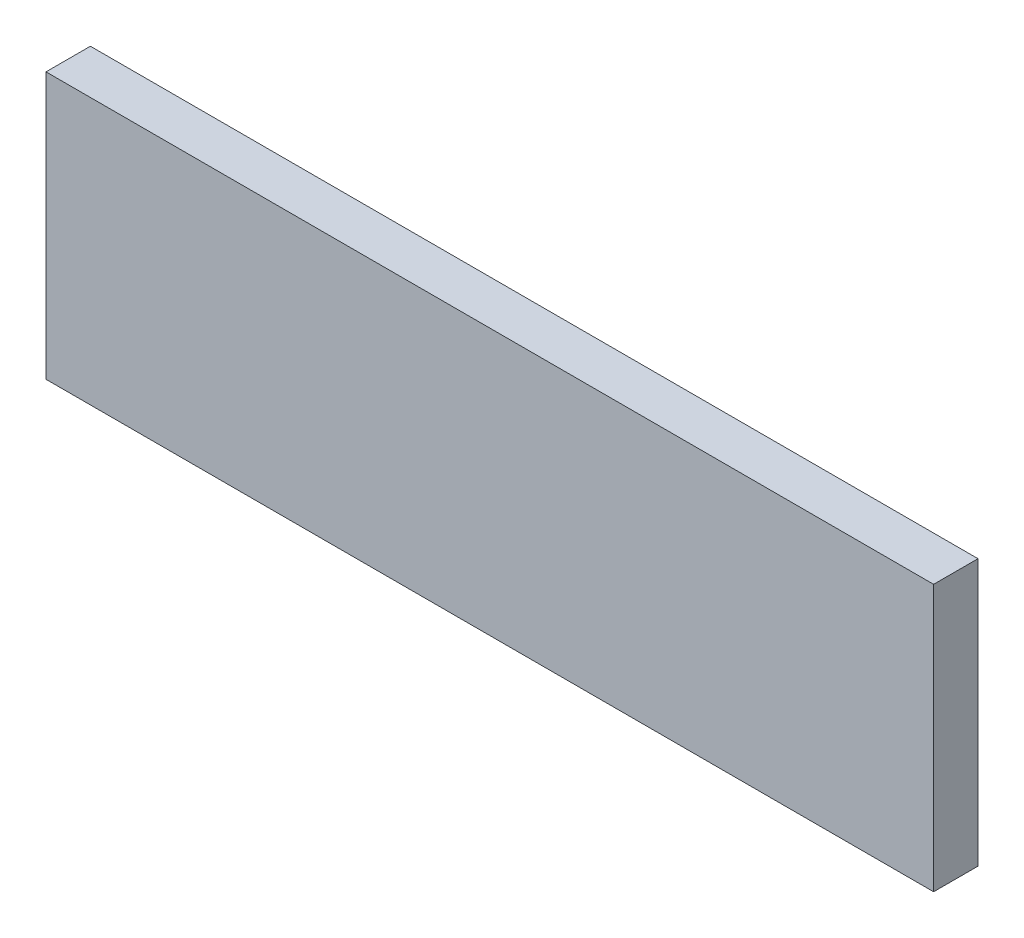
SolidWorks part; units mm, degrees
ref_plane "Front Plane" through (0, 0, 0) normal (0, 0, 1) x (1, 0, 0)
ref_plane "Top Plane" through (0, 0, 0) normal (0, 1, 0) x (1, 0, 0)
ref_plane "Right Plane" through (0, 0, 0) normal (1, 0, 0) x (0, 0, -1)
sketch "Sketch1" plane through (0, 0, 0) normal (0, 1, 0) x (1, 0, 0)
  line L0 (129.3552, 20.4513) -> (-20.6448, 20.4513) construction
  line L1 (-10.6448, 0.4513) -> (89.3552, 0.4513)
  line L2 (-10.6448, 0.4513) -> (-10.6448, -4.5487)
  line L3 (-10.6448, -4.5487) -> (89.3552, -4.5487)
  line L4 (89.3552, 0.4513) -> (89.3552, -4.5487)
  line L6 (129.3552, -61.5487) -> (129.3552, 20.4513) construction
  dimension "D1" = 5
  dimension "D2" = 100
  dimension "D3" = 20
  dimension "D4" = 40
extrude "Boss-Extrude1" add sketch "Sketch1" along normal blind 30
